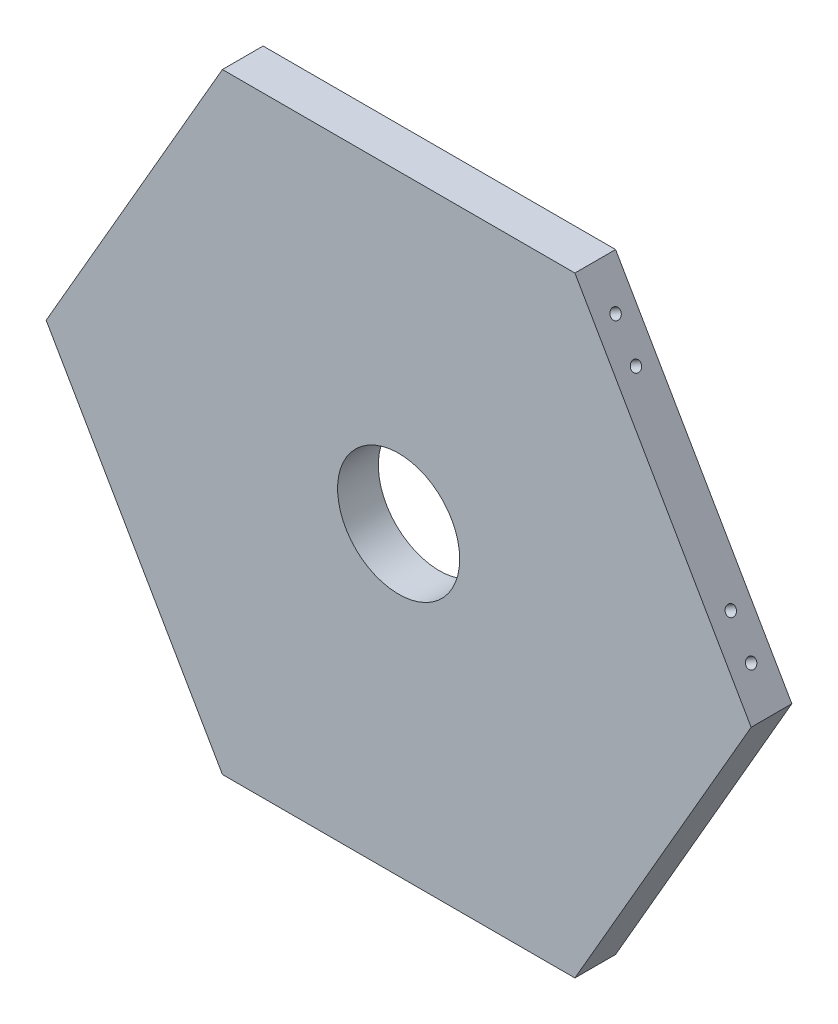
SolidWorks part; units mm, degrees
ref_plane "Top Plane" through (0, 0, 0) normal (0, 0, 1) x (1, 0, 0)
ref_plane "Front Plane" through (0, 0, 0) normal (0, 1, 0) x (1, 0, 0)
ref_plane "Right Plane" through (0, 0, 0) normal (1, 0, 0) x (0, 0, -1)
sketch "Sketch1" plane through (0, 0, 0) normal (0, 0, 1) x (1, 0, 0)
  line L0 (0, 0) -> (163.1642, 0) construction
  line L1 (43.3013, -75) -> (86.6025, 0)
  line L2 (86.6025, 0) -> (43.3013, 75)
  line L3 (43.3013, 75) -> (-43.3013, 75)
  line L4 (-43.3013, 75) -> (-86.6025, 0)
  line L5 (-86.6025, 0) -> (-43.3013, -75)
  line L6 (-43.3013, -75) -> (43.3013, -75)
  circle A0 centre (0, 0) radius 75 construction
  dimension "D1" = 150
extrude "Boss-Extrude1" add sketch "Sketch1" along normal blind 10
sketch "Sketch2" plane through (0, -75, 0) normal (0, -1, 0) x (1, 0, 0)
  line L0 (-43.3013, 10) -> (-43.3013, 0) construction
  line L1 (-43.3013, 0) -> (43.3013, 0) construction
  line L2 (0, 0) -> (0, 18.7567) construction
  circle A0 centre (-33.3013, 5) radius 1.25
  circle A1 centre (-23.3013, 5) radius 1.25
  circle A2 centre (33.3013, 5) radius 1.25
  circle A3 centre (23.3013, 5) radius 1.25
  dimension "D1" = 2.5
  dimension "D3" = 10
  dimension "D2" = 10
  dimension "D4" = 5
extrude "Cut-Extrude1" cut sketch "Sketch2" against normal blind 5
pattern_circular "CirPattern1" count 3 over 360 about axis through (0, 0, 0) along (0, 0, 1) of "Cut-Extrude1"
sketch "Sketch3" plane through (0, 0, 10) normal (0, 0, 1) x (1, 0, 0)
  circle A0 centre (0, 0) radius 15
  dimension "D1" = 30
extrude "Cut-Extrude2" cut sketch "Sketch3" against normal blind 10
